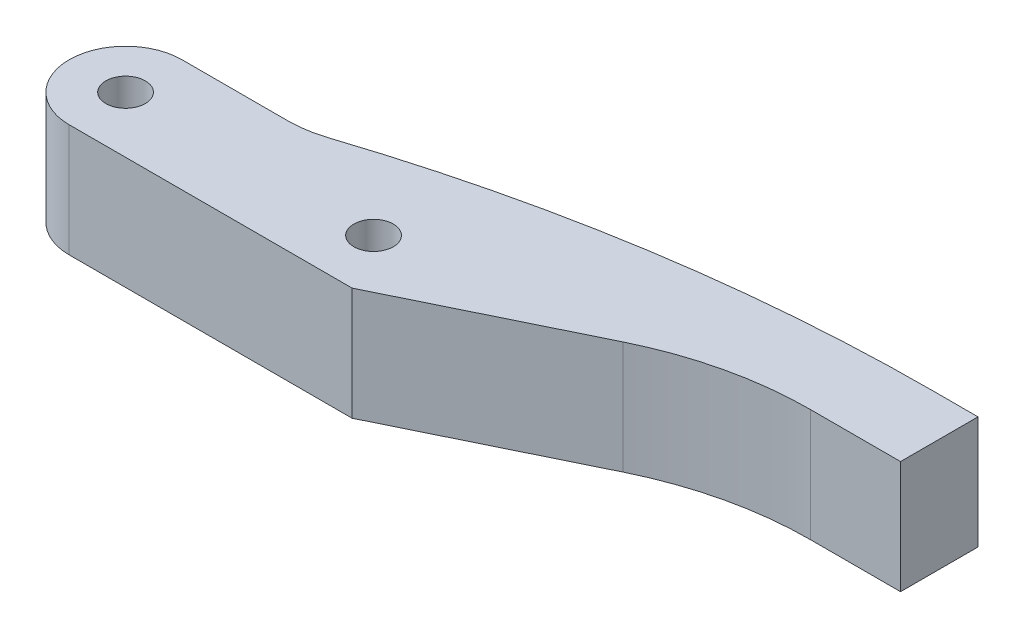
SolidWorks part; units mm, degrees
ref_plane "前视基准面" through (0, 0, 0) normal (0, 0, 1) x (1, 0, 0)
ref_plane "上视基准面" through (0, 0, 0) normal (0, 1, 0) x (1, 0, 0)
ref_plane "右视基准面" through (0, 0, 0) normal (1, 0, 0) x (0, 0, -1)
sketch "草图1" plane through (0, 0, 0) normal (0, 1, 0) x (1, 0, 0)
  line L0 (0, 0) -> (22, 0) construction
  line L2 (-5, 5) -> (27, 5)
  line L3 (-5, 5) -> (-5, -5)
  line L4 (-5, -5) -> (27, -5)
  line L5 (27, 5) -> (27, -5)
  line L6 (11, -5) -> (11, 5) construction
  line L7 (-5, 0) -> (27, 0) construction
  circle A0 centre (0, 0) radius 5
  circle A1 centre (0, 0) radius 1.75
  circle A2 centre (22, 0) radius 1.75
  circle A3 centre (22, 0) radius 5
  point P7 (11, 0)
  dimension "D1" = 10
  dimension "D2" = 3.5
  dimension "D3" = 22
extrude "凸台-拉伸1" add sketch "草图1" along normal blind 10 contours A0 A1 | A3 L2 A0 L4 | A3 A2
sketch "草图2" plane through (0, 10, 0) normal (0, 1, 0) x (1, 0, 0)
  line L0 (22, -5) -> (25.092, -5)
  line L1 (25.092, -5) -> (41.2597, 2.8855)
  line L2 (62.75, 6) -> (62.75, 12.87)
  line L3 (62.75, 12.87) -> (58.75, 12.87)
  line L4 (0, 5) -> (22, 5) construction
  line L5 (0, -5) -> (22, -5) construction
  line L6 (62.75, 6) -> (54.75, 6)
  line L9 (0, -5) -> (22, -5)
  line L10 (22, 5) -> (0, 5)
  line L12 (22, 5) -> (11, 5)
  arc A0 (54.75, 6) -> (41.2597, 2.8855) centre (54.75, -24.7737) ccw
  arc A1 (58.75, 12.87) -> (11, 5) centre (58.75, -135.9228) ccw
  circle A2 centre (22, 0) radius 1.75 construction
  arc A5 (0, 5) -> (0, -5) centre (0, 0) ccw
  arc A6 (22, -5) -> (22, 5) centre (22, 0) ccw
  arc A8 (22, -5) -> (22, 5) centre (22, 0) ccw
  point P23 (62.75, 6)
  dimension "D1" = 17.87
  dimension "D2" = 11
  dimension "D3" = 4
  dimension "D4" = 26
  dimension "D5" = 36.75
  dimension "D6" = 47.75
  dimension "D7" = 8
  dimension "D8" = 0
extrude "凸台-拉伸2" add sketch "草图2" against normal blind 10
fillet "圆角1" radius 10 1 edges at (11, 5, -5)
